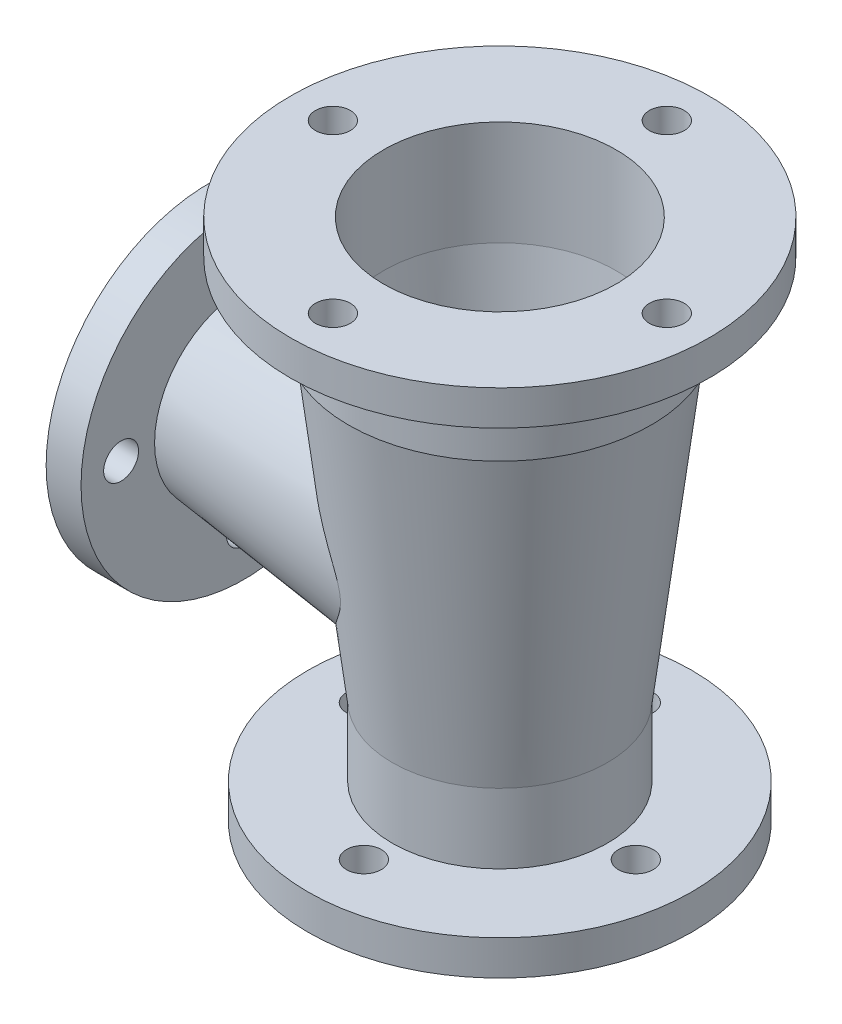
SolidWorks part; units mm, degrees
ref_plane "Front Plane" through (0, 0, 0) normal (0, 0, 1) x (1, 0, 0)
ref_plane "Top Plane" through (0, 0, 0) normal (0, 1, 0) x (1, 0, 0)
ref_plane "Right Plane" through (0, 0, 0) normal (1, 0, 0) x (0, 0, -1)
sketch "Sketch2" plane through (0, 0, 0) normal (0, 0, 1) x (1, 0, 0)
  line L0 (0, 219.6899) -> (0, -142.4862) construction
  line L1 (-213.4455, 0) -> (202.092, 0) construction
  line L2 (20, 0) -> (66, 0)
  line L3 (66, 0) -> (66, 12)
  line L4 (66, 12) -> (37, 12)
  line L5 (37, 12) -> (37, 36)
  line L8 (52, 168) -> (72, 168)
  line L9 (72, 168) -> (72, 180)
  line L10 (72, 180) -> (40, 180)
  line L12 (27, 36) -> (20, 36)
  line L13 (20, 36) -> (20, 0)
  line L14 (50, 144) -> (52, 144)
  line L15 (52, 144) -> (52, 168)
  line L16 (40, 180) -> (40, 144)
  line L17 (40, 144) -> (27, 36)
  line L18 (37, 36) -> (50, 144)
  point P5 (-154.992, 91.1253)
  point P18 (52, 156)
  point P22 (66, 6)
  dimension "D1" = 144
  dimension "D2" = 36
  dimension "D3" = 36
  dimension "D4" = 12
  dimension "D5" = 66
  dimension "D6" = 40
  dimension "D7" = 72
  dimension "D8" = 36
  dimension "D9" = 10
  dimension "D10" = 12
  dimension "D11" = 20
  dimension "D12" = 10
  dimension "D13" = 27
  dimension "D15" = 52
revolve "Revolve1" add sketch "Sketch2" angle 360 about L0
sketch "Sketch3" plane through (0, 0, 0) normal (0, 0, 1) x (1, 0, 0)
  line L0 (0, -13.6796) -> (0, 188.6527) construction
  line L1 (-132.488, 84) -> (89.7005, 84) construction
  line L2 (0, 42.72) -> (0, 52)
  line L3 (0, 52) -> (-100, 64)
  line L4 (-100, 64) -> (-100, 28)
  line L5 (-100, 28) -> (-88, 28)
  line L6 (-88, 28) -> (-88, 53.28)
  line L7 (-88, 53.28) -> (0, 42.72)
  line L8 (-66, 0) -> (66, 0) construction
  point P7 (-44, 48)
  point P12 (-50, 58)
  dimension "D1" = 12
  dimension "D2" = 56
  dimension "D3" = 20
  dimension "D4" = 100
  dimension "D5" = 10
  dimension "D6" = 26
  dimension "D7" = 84
revolve "Revolve2" add sketch "Sketch3" angle 360 about L1
sketch "Sketch9" plane through (-100, 0, 0) normal (-1, 0, 0) x (0, 0, 1)
  line L0 (0, -13.4282) -> (0, 187.6473) construction
  line L1 (-91.0727, 83.0881) -> (83.1965, 84.8412) construction
  circle A0 centre (0, 123.8058) radius 6
  circle A1 centre (-38.8944, 83.613) radius 6
  circle A2 centre (0, 44.0513) radius 6
  circle A3 centre (42.2245, 84.429) radius 6
  dimension "D1" = 12
  dimension "D3" = 12
  dimension "D4" = 12
  dimension "D5" = 12
  dimension "D2" = 84
extrude "Cut-Extrude1" cut sketch "Sketch9" against normal up to surface (12 mm away) and the other way through all up to face at (-88, 84, 30.72)
sketch "Sketch10" plane through (0, 0, 0) normal (0, -1, 0) x (1, 0, 0)
  line L0 (0, -79.9275) -> (0, 76.1071) construction
  line L1 (90.9614, 0) -> (-112.3259, 0) construction
  circle A0 centre (0, 46.7501) radius 6
  circle A1 centre (46.7501, 0) radius 6
  circle A2 centre (0, -46.7501) radius 6
  circle A3 centre (-46.7501, 0) radius 6
  point P16 (0, 0)
  dimension "D1" = 12
  dimension "D2" = 4
extrude "Cut-Extrude2" cut sketch "Sketch10" against normal up to surface (12 mm away) up to face at (0, 12, 37)
sketch "Sketch11" plane through (0, 180, 0) normal (0, 1, 0) x (1, 0, 0)
  line L0 (0, -80.5308) -> (0, 77.5146) construction
  circle A0 centre (0, 57.4071) radius 6
  circle A1 centre (57.4071, 0) radius 6
  circle A2 centre (0, -57.4071) radius 6
  circle A3 centre (-57.4071, 0) radius 6
  point P14 (0, 0)
  dimension "D1" = 12
  dimension "D2" = 4
extrude "Cut-Extrude3" cut sketch "Sketch11" against normal up to surface (12 mm away) up to face at (0, 168, 72)
